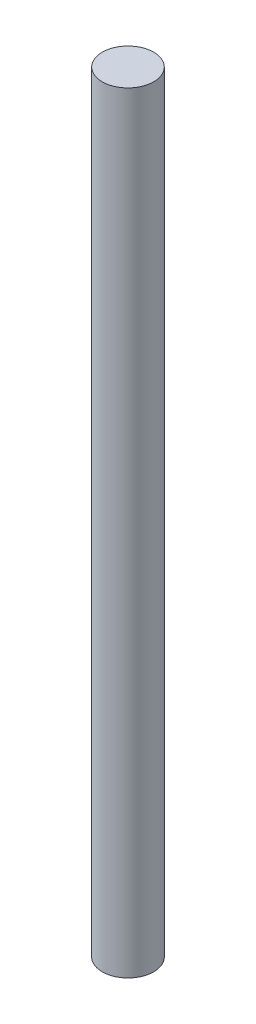
SolidWorks part; units mm, degrees
ref_plane "Front Plane" through (0, 0, 0) normal (0, 0, 1) x (1, 0, 0)
ref_plane "Top Plane" through (0, 0, 0) normal (0, 1, 0) x (1, 0, 0)
ref_plane "Right Plane" through (0, 0, 0) normal (1, 0, 0) x (0, 0, -1)
sketch "Sketch2" plane through (0, 0, 0) normal (0, 1, 0) x (1, 0, 0)
  circle A0 centre (0, 0) radius 4
  dimension "D1" = 8
extrude "Boss-Extrude1" add sketch "Sketch2" along normal blind 120
